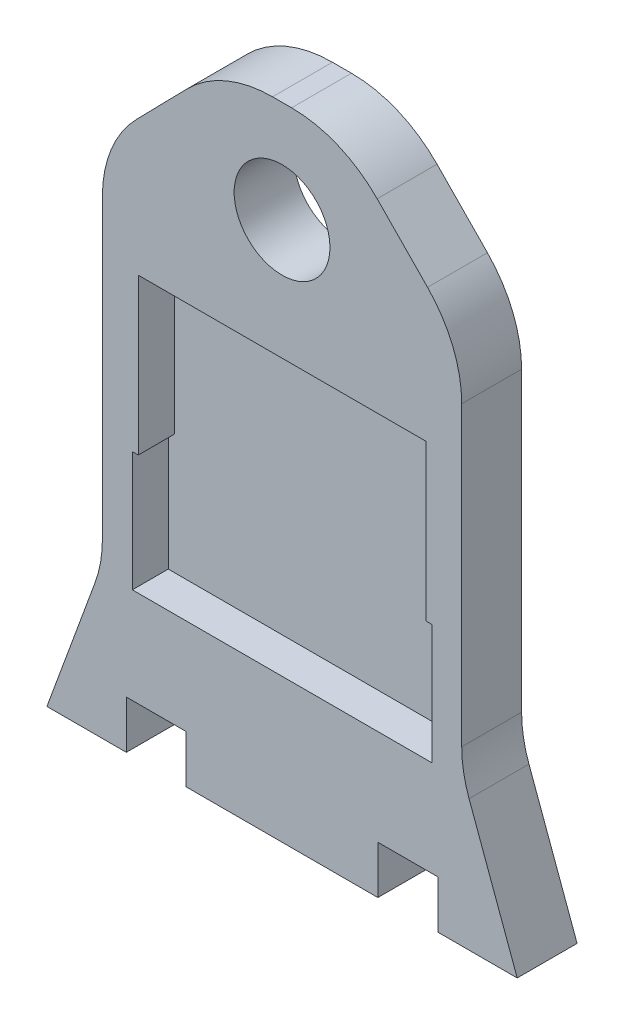
SolidWorks part; units mm, degrees
ref_plane "Plan de face" through (0, 0, 0) normal (0, 0, 1) x (1, 0, 0)
ref_plane "Plan de dessus" through (0, 0, 0) normal (0, 1, 0) x (1, 0, 0)
ref_plane "Plan de droite" through (0, 0, 0) normal (1, 0, 0) x (0, 0, -1)
sketch "Esquisse1" plane through (0, 0, 0) normal (0, 0, 1) x (1, 0, 0)
  line L0 (0, 33.5) -> (0, -8.5) construction
  line L1 (-15, -33.5) -> (15, -33.5)
  line L2 (-15, -33.5) -> (-15, 33.5)
  line L3 (-15, 33.5) -> (15, 33.5)
  line L4 (15, -33.5) -> (15, 33.5)
  line L5 (-15, -33.5) -> (15, 33.5) construction
  line L6 (-15, 33.5) -> (15, -33.5) construction
  circle A1 centre (0, 12.5) radius 4
  point P0 (0, 0)
  dimension "D3" = 42
  dimension "D4" = 8
  dimension "D1" = 67
  dimension "D2" = 30
extrude "Boss.-Extru.1" add sketch "Esquisse1" along normal blind 5
sketch "Esquisse2" plane through (0, 0, 5) normal (0, 0, 1) x (1, 0, 0)
  line L0 (15, -33.5) -> (15, 33.5) construction
  line L1 (-15, 33.5) -> (15, 33.5)
  line L2 (-15, 33.5) -> (-15, 21)
  line L3 (-15, 21) -> (15, 21)
  line L4 (15, 33.5) -> (15, 21)
  dimension "D1" = 12.5
extrude "Enlèv. mat.-Extru.1" cut sketch "Esquisse2" against normal blind 5
sketch "Esquisse3" plane through (0, 0, 5) normal (0, 0, 1) x (1, 0, 0)
  line L0 (0, -33.5) -> (8, -33.5) construction
  line L1 (-15, -33.5) -> (15, -33.5) construction
  line L2 (8, -33.5) -> (13, -33.5) construction
  line L3 (0, -33.5) -> (-8, -33.5) construction
  line L4 (-8, -33.5) -> (-13, -33.5) construction
  line L6 (-13, -33.5) -> (-8, -33.5)
  line L7 (-13, -33.5) -> (-13, -28.5)
  line L8 (-13, -28.5) -> (-8, -28.5)
  line L9 (-8, -33.5) -> (-8, -28.5)
  line L10 (8, -33.5) -> (13, -33.5)
  line L11 (8, -33.5) -> (8, -28.5)
  line L12 (8, -28.5) -> (13, -28.5)
  line L13 (13, -33.5) -> (13, -28.5)
  dimension "D1" = 8
  dimension "D2" = 5
  dimension "D3" = 8
  dimension "D4" = 5
  dimension "D5" = 5
  dimension "D6" = 5
extrude "Enlèv. mat.-Extru.2" cut sketch "Esquisse3" against normal through all
sketch "Esquisse5" plane through (0, 0, 5) normal (0, 0, 1) x (1, 0, 0)
  line L0 (-15, -6.25) -> (-15, -33.5) construction
  line L1 (-15, 21) -> (-15, -33.5) construction
  line L2 (-15, -19.875) -> (-20, -33.5)
  line L3 (15, -33.5) -> (15, -6.25) construction
  line L4 (15, -33.5) -> (15, 21) construction
  line L5 (-20, -33.5) -> (-15, -33.5)
  line L6 (15, -19.875) -> (20, -33.5)
  line L7 (20, -33.5) -> (15, -33.5)
  line L8 (-15, -19.875) -> (-15, -33.5)
  line L9 (15, -33.5) -> (15, -19.875)
  dimension "D1" = 5
  dimension "D2" = 5
extrude "Boss.-Extru.2" add sketch "Esquisse5" against normal blind 5
sketch "Esquisse6" plane through (0, 0, 5) normal (0, 0, 1) x (1, 0, 0)
  line L0 (-15, 21) -> (-15, 0.5625) construction
  line L1 (-15, 21) -> (-15, -19.875) construction
  line L2 (15, 0.5625) -> (15, 21) construction
  line L3 (15, -19.875) -> (15, 21) construction
  line L4 (-15, 10.7813) -> (-5, 21)
  line L5 (-5, 21) -> (-15, 21)
  line L6 (-15, 21) -> (-15, 10.7813)
  line L7 (15, 10.7813) -> (5, 21)
  line L8 (-15, 21) -> (15, 21) construction
  line L9 (5, 21) -> (15, 21)
  line L10 (15, 21) -> (15, 10.7813)
  dimension "D1" = 10
  dimension "D2" = 10
extrude "Enlèv. mat.-Extru.3" cut sketch "Esquisse6" against normal through all
sketch "Esquisse8" plane through (0, 0, 5) normal (0, 0, 1) x (1, 0, 0)
  line L1 (-20, -33.5) -> (21.1134, -33.5)
  line L2 (-20, -33.5) -> (-20, -32.5)
  line L3 (-20, -32.5) -> (21.1134, -32.5)
  line L4 (21.1134, -33.5) -> (21.1134, -32.5)
  dimension "D1" = 1
extrude "Enlèv. mat.-Extru.4" cut sketch "Esquisse8" against normal through all
fillet "Congé1" radius 10 4 edges at (15, 10.7813, 2.5) (-15, 10.7813, 2.5) (5, 21, 2.5) (-5, 21, 2.5)
fillet "Congé2" radius 10 2 edges at (-15, -19.875, 2.5) (15, -19.875, 2.5)
sketch "Esquisse9" plane through (0, 0, 5) normal (0, 0, 1) x (1, 0, 0)
  line L0 (0, 8.1647) -> (0, -29.2147) construction
  line L2 (-12, 2.5) -> (12, 2.5)
  line L3 (-12, 2.5) -> (-12, -10.5)
  line L4 (-12, -10.5) -> (12, -10.5)
  line L5 (12, 2.5) -> (12, -10.5)
  line L6 (-12, 2.5) -> (12, -10.5) construction
  line L7 (-12, -10.5) -> (12, 2.5) construction
  line L8 (-12.5, -20.5) -> (12.5, -20.5)
  line L9 (-12.5, -20.5) -> (-12.5, -10.5)
  line L10 (-12.5, -10.5) -> (12.5, -10.5)
  line L11 (12.5, -20.5) -> (12.5, -10.5)
  line L12 (-12.5, -20.5) -> (12.5, -10.5) construction
  line L13 (-12.5, -10.5) -> (12.5, -20.5) construction
  circle A0 centre (0, 12.5) radius 4 construction
  point P3 (0, -4)
  point P10 (0, -15.5)
  dimension "D1" = 24
  dimension "D2" = 13
  dimension "D3" = 10
  dimension "D4" = 25
  dimension "D5" = 10
  dimension "D6" = 0
extrude "Enlèv. mat.-Extru.5" cut sketch "Esquisse9" against normal blind 3 contours L5 L2 L3 L4 | L8 L11 L10 L4 L9
